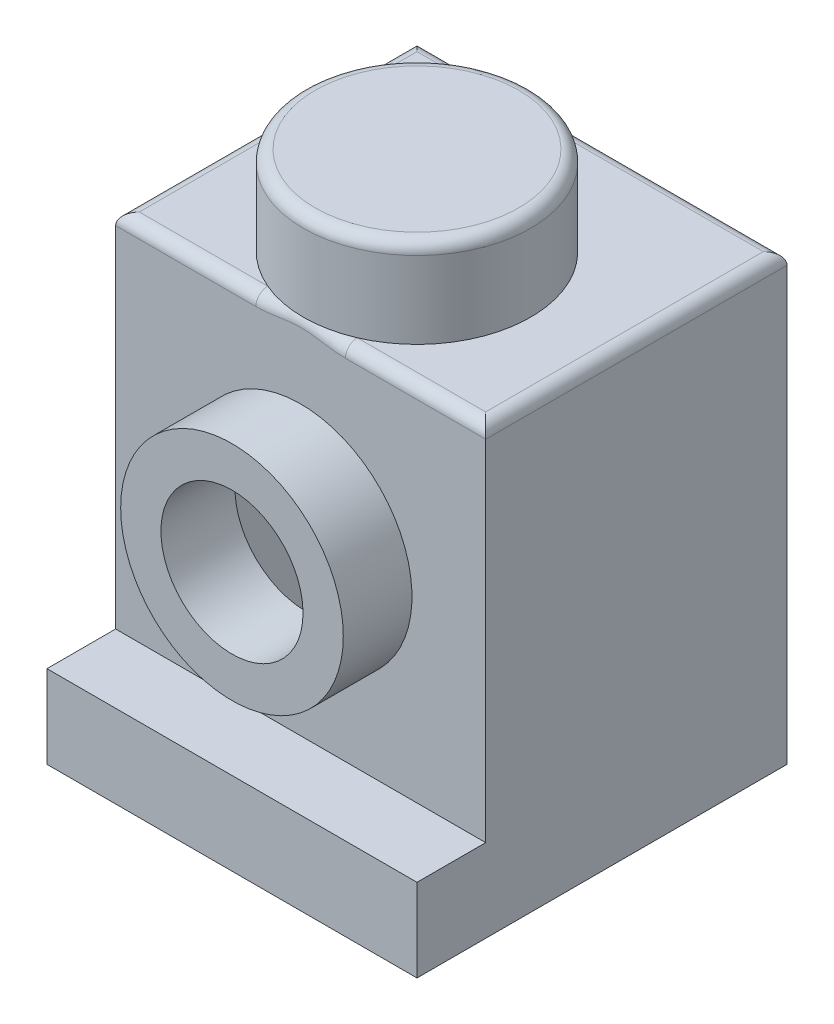
SolidWorks part; units mm, degrees
ref_plane "Front" through (0, 0, 0) normal (0, 0, 1) x (1, 0, 0)
ref_plane "Top" through (0, 0, 0) normal (0, 1, 0) x (1, 0, 0)
ref_plane "Right" through (0, 0, 0) normal (1, 0, 0) x (0, 0, -1)
sketch "Sketch1" plane through (0, 0, 0) normal (0, 1, 0) x (1, 0, 0)
  line L0 (0, 0) -> (0, 50.4571) construction
  line L1 (0, 0) -> (55.8847, 0) construction
  line L2 (-3.9688, 3.9687) -> (3.9688, 3.9687)
  line L3 (-3.9688, 3.9687) -> (-3.9688, -3.9687)
  line L4 (3.9688, -3.9687) -> (-3.9688, -3.9687)
  line L5 (3.9688, -3.9687) -> (3.9688, 3.9687)
  dimension "Length" = 7.9375
  dimension "Width" = 7.9375
extrude "Base-Extrude" add sketch "Sketch1" along normal blind 9.525
sketch "Sketch2" plane through (0, 9.525, 0) normal (0, 1, 0) x (-1, 0, 0)
  line L0 (3.9688, -3.9687) -> (3.9688, 3.9687) construction
  line L1 (-3.9688, 3.9687) -> (3.9688, 3.9687) construction
  circle A0 centre (0, 0) radius 2.4384
  dimension "DotDiam" = 4.8768
  dimension "DotLSpc" = 3.9688
  dimension "DotWSpc" = 3.9688
extrude "Boss-Extrude1" add sketch "Sketch2" along normal blind 1.905
sketch "Sketch3" plane through (3.9688, 0, 0) normal (1, 0, 0) x (0, 0, -1)
  line L0 (-3.9687, 9.525) -> (-2.4955, 9.525)
  line L1 (-3.9687, 9.525) -> (-3.9687, 1.778)
  line L2 (-2.4955, 1.778) -> (-3.9687, 1.778)
  line L3 (-2.4955, 1.778) -> (-2.4955, 9.525)
  line L4 (-3.9687, 0) -> (3.9687, 0) construction
  dimension "D1" = 1.4732
  dimension "D2" = 1.778
extrude "Cut-Extrude1" cut sketch "Sketch3" against normal through all
fillet "Fillet1" radius 0.254 5 edges at (0, 9.525, -3.9687) (0, 11.43, 2.4384) (3.9688, 9.525, -0.7366) (0, 9.525, 2.4955) (-3.9688, 9.525, -0.7366)
sketch "Sketch4" plane through (0, 0, 0) normal (0, -1, 0) x (1, 0, 0)
  line L4 (-2.3813, 2.3812) -> (-2.3813, -2.3812)
  line L5 (-2.3813, -2.3812) -> (2.3813, -2.3812)
  line L6 (2.3813, -2.3812) -> (2.3813, 2.3812)
  line L7 (2.3813, 2.3812) -> (-2.3813, 2.3812)
  line L8 (-2.3813, 2.3812) -> (-2.3813, -2.3812)
  line L9 (-2.3813, -2.3812) -> (2.3813, -2.3812)
  line L10 (2.3813, -2.3812) -> (2.3813, 2.3812)
  line L11 (2.3813, 2.3812) -> (-2.3813, 2.3812)
  dimension "D1" = 1.5875
extrude "Cut-Extrude2" cut sketch "Sketch4" against normal offset from surface (7.9375 mm away) 1.5875
sketch "Sketch5" plane through (0, 0, -3.9687) normal (0, 0, -1) x (-1, 0, 0)
  line L0 (2.3813, 7.9375) -> (2.3813, 3.175)
  line L1 (-2.3813, 7.9375) -> (-2.3813, 3.175)
  line L2 (2.3813, 3.175) -> (-2.3813, 3.175)
  line L3 (3.9688, 9.271) -> (3.9688, 0) construction
  line L4 (-3.9688, 9.271) -> (-3.9688, 0) construction
  line L5 (-3.7147, 9.525) -> (3.7147, 9.525) construction
  line L9 (2.3813, 7.9375) -> (-2.3813, 7.9375)
  dimension "D1" = 1.5875
  dimension "D2" = 1.5875
  dimension "D3" = 1.5875
extrude "Cut-Extrude3" cut sketch "Sketch5" against normal up to next
sketch "Sketch6" plane through (0, 0, 2.4955) normal (0, 0, 1) x (1, 0, 0)
  line L0 (-2.3813, 7.9375) -> (2.3813, 3.175) construction
  circle A0 centre (0, 5.5563) radius 2.3876
  dimension "D1" = 4.7752
extrude "Boss-Extrude2" add sketch "Sketch6" along normal up to surface (1.4732 mm away)
sketch "Sketch7" plane through (0, 0, 3.9687) normal (0, 0, 1) x (1, 0, 0)
  circle A0 centre (0, 5.5563) radius 1.524
  dimension "D1" = 3.048
extrude "Cut-Extrude4" cut sketch "Sketch7" against normal up to next
